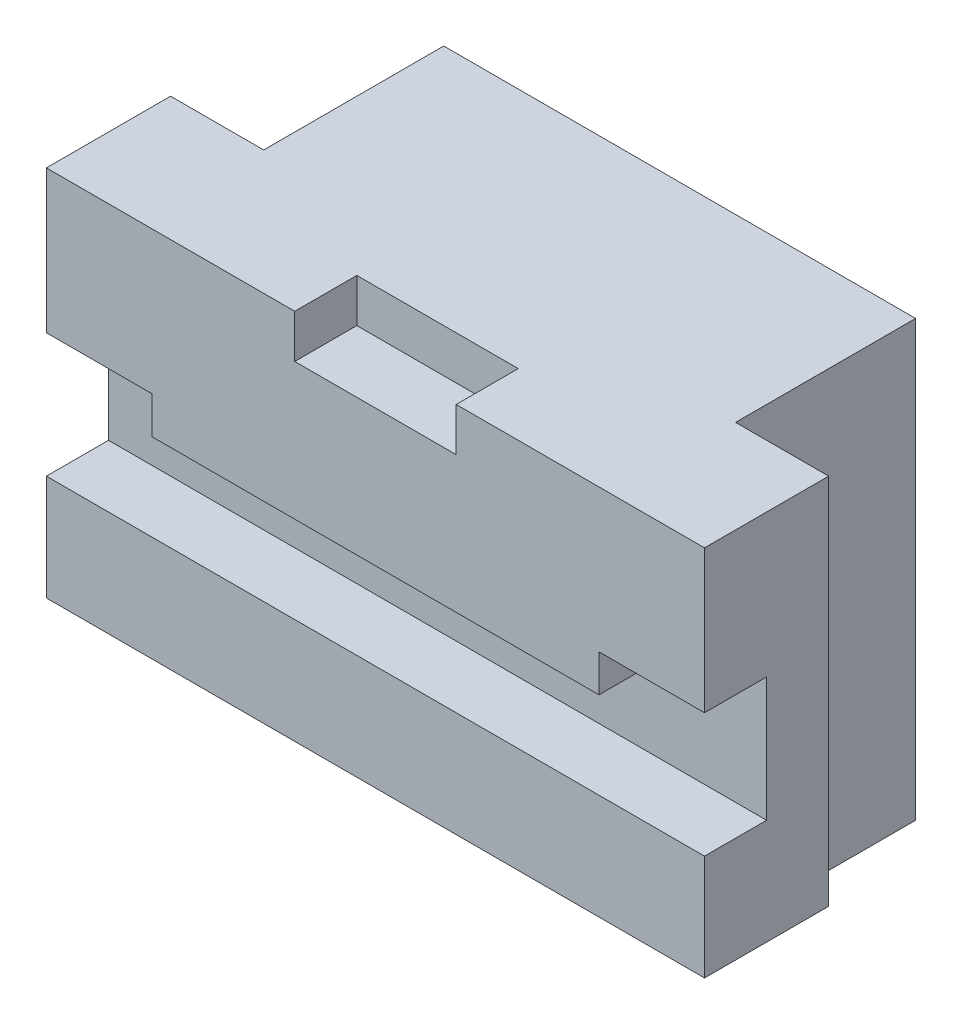
SolidWorks part; units mm, degrees
ref_plane "Спереди" through (0, 0, 0) normal (0, 0, 1) x (1, 0, 0)
ref_plane "Сверху" through (0, 0, 0) normal (0, 1, 0) x (1, 0, 0)
ref_plane "Справа" through (0, 0, 0) normal (1, 0, 0) x (0, 0, -1)
sketch "Эскиз1" plane through (0, 0, 0) normal (0, 0, 1) x (1, 0, 0)
  line L1 (-26.5, -30) -> (26.5, -30)
  line L2 (-26.5, -30) -> (-26.5, 30)
  line L3 (-26.5, 30) -> (26.5, 30)
  line L4 (26.5, -30) -> (26.5, 30)
  line L5 (-26.5, -30) -> (26.5, 30) construction
  line L6 (-26.5, 30) -> (26.5, -30) construction
  line L7 (-26.5, 30) -> (-13.5, 30)
  line L8 (-26.5, 30) -> (-26.5, 23)
  line L9 (-26.5, 23) -> (-13.5, 23)
  line L10 (-13.5, 30) -> (-13.5, 23)
  line L11 (26.5, 7) -> (9.5, 7)
  line L12 (26.5, 7) -> (26.5, -13)
  line L13 (26.5, -13) -> (9.5, -13)
  line L14 (9.5, 7) -> (9.5, -13)
  line L15 (9.5, -13) -> (-26.5, -13)
  line L16 (9.5, -13) -> (9.5, 1)
  line L17 (9.5, 1) -> (-26.5, 1)
  line L18 (-26.5, -13) -> (-26.5, 1)
  point P0 (0, 0)
  dimension "D1" = 60
  dimension "D2" = 53
  dimension "D3" = 13
  dimension "D4" = 7
  dimension "D5" = 23
  dimension "D6" = 20
  dimension "D7" = 17
  dimension "D8" = 14
extrude "Бобышка-Вытянуть1" add sketch "Эскиз1" along normal blind 10 contours L17 L14 L11 L4 L3 L10 L9 L2 | L13 L15 L2 L1 L4
sketch "Эскиз2" plane through (0, 0, 0) normal (0, 0, -1) x (-1, 0, 0)
  line L0 (-26.5, -30) -> (-26.5, 30)
  line L1 (-26.5, 30) -> (13.5, 30)
  line L2 (13.5, 30) -> (13.5, 23)
  line L3 (13.5, 23) -> (26.5, 23)
  line L4 (26.5, 23) -> (26.5, -30)
  line L5 (26.5, -30) -> (-26.5, -30)
extrude "Бобышка-Вытянуть2" add sketch "Эскиз2" along normal blind 10
sketch "Эскиз3" plane through (0, 0, -10) normal (0, 0, -1) x (-1, 0, 0)
  line L0 (13.5, 30) -> (-26.5, 30) construction
  line L1 (26.5, 30) -> (-11.5, 30)
  line L2 (26.5, 30) -> (26.5, -40)
  line L3 (26.5, -40) -> (-11.5, -40)
  line L4 (-11.5, 30) -> (-11.5, -40)
  line L5 (26.5, -30) -> (26.5, 23) construction
  dimension "D1" = 70
  dimension "D2" = 38
extrude "Бобышка-Вытянуть3" add sketch "Эскиз3" along normal blind 9
sketch "Эскиз4" plane through (11.5, 0, 0) normal (1, 0, 0) x (0, 0, -1)
  line L0 (10, -40) -> (-10, -30)
  line L1 (-10, -30) -> (10, -30)
  line L2 (10, -30) -> (10, -40)
extrude "Бобышка-Вытянуть4" add sketch "Эскиз4" against normal up to surface (38 mm away) up to face at (-26.5, -6.125, -2.75)
mirror "Зеркальное отражение1" about plane through (-26.5, 0, 10) normal (-1, 0, 0) of bodies 109
sketch "Эскиз5" plane through (0, 0, -10) normal (0, 0, 1) x (1, 0, 0)
  line L4 (-13.5, 30) -> (-39.5, 30)
  line L5 (-39.5, 30) -> (-39.5, 23)
  line L6 (-39.5, 23) -> (-13.5, 23)
  line L7 (-13.5, 23) -> (-13.5, 30)
  line L8 (-13.5, 30) -> (-39.5, 30)
  line L9 (-39.5, 30) -> (-39.5, 23)
  line L10 (-39.5, 23) -> (-13.5, 23)
  line L11 (-13.5, 23) -> (-13.5, 30)
  dimension "D1" = 0
extrude "Бобышка-Вытянуть5" add sketch "Эскиз5" along normal blind 10
sketch "Эскиз6" plane through (0, 0, -19) normal (0, 0, -1) x (-1, 0, 0)
  line L4 (-11.5, -40) -> (64.5, -40)
  line L5 (64.5, -40) -> (64.5, 30)
  line L6 (64.5, 30) -> (-11.5, 30)
  line L7 (-11.5, 30) -> (-11.5, -40)
  line L8 (-11.5, -40) -> (64.5, -40)
  line L9 (64.5, -40) -> (64.5, 30)
  line L10 (64.5, 30) -> (-11.5, 30)
  line L11 (-11.5, 30) -> (-11.5, -40)
  dimension "D1" = 0
extrude "Бобышка-Вытянуть6" add sketch "Эскиз6" along normal blind 20
